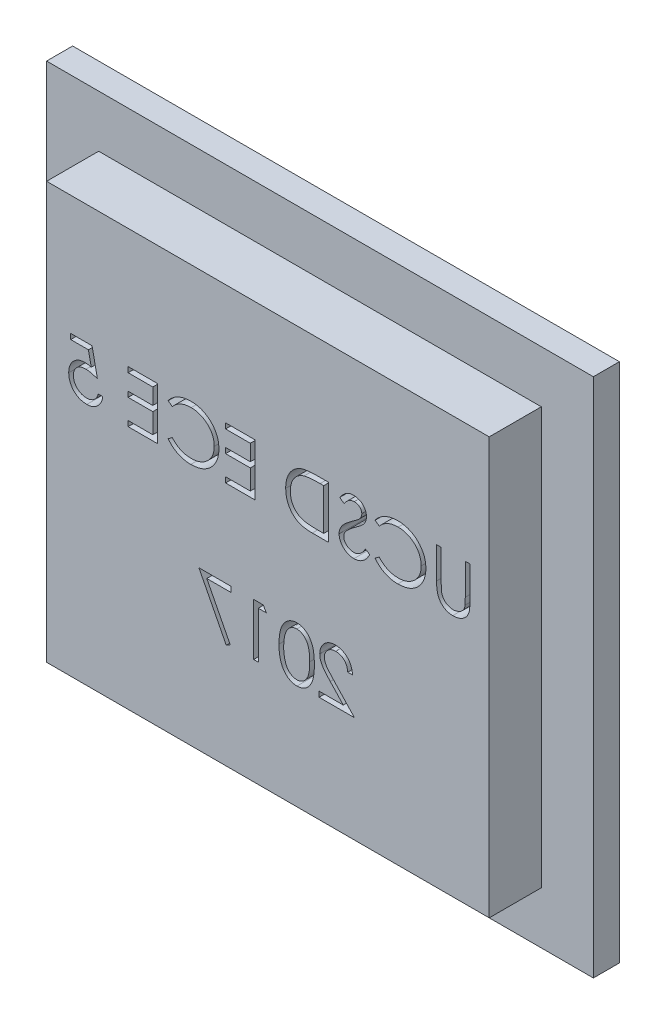
SolidWorks part; units mm, degrees
ref_plane "Front Plane" through (0, 0, 0) normal (0, 0, 1) x (1, 0, 0)
ref_plane "Top Plane" through (0, 0, 0) normal (0, 1, 0) x (1, 0, 0)
ref_plane "Right Plane" through (0, 0, 0) normal (1, 0, 0) x (0, 0, -1)
sketch "Sketch1" plane through (0, 0, 0) normal (0, 0, 1) x (1, 0, 0)
  line L1 (-5.25, -5) -> (5.25, -5)
  line L2 (-5.25, -5) -> (-5.25, 5)
  line L3 (-5.25, 5) -> (5.25, 5)
  line L4 (5.25, -5) -> (5.25, 5)
  line L5 (-5.25, -5) -> (5.25, 5) construction
  line L6 (-5.25, 5) -> (5.25, -5) construction
  point P0 (0, 0)
  dimension "D1" = 10
  dimension "D2" = 10.5
extrude "Boss-Extrude1" add sketch "Sketch1" along normal blind 0.5
sketch "Sketch2" plane through (0, 0, 0.5) normal (0, 0, 1) x (1, 0, 0)
  line L1 (-4.25, -4) -> (4.25, -4)
  line L2 (-4.25, -4) -> (-4.25, 4)
  line L3 (-4.25, 4) -> (4.25, 4)
  line L4 (4.25, -4) -> (4.25, 4)
  line L5 (-4.25, -4) -> (4.25, 4) construction
  line L6 (-4.25, 4) -> (4.25, -4) construction
  point P0 (0, 0)
  dimension "D1" = 8
  dimension "D2" = 8.5
extrude "Boss-Extrude2" add sketch "Sketch2" along normal blind 1
sketch "Sketch3" plane through (0, 0, 0) normal (0, 0, -1) x (-1, 0, 0)
  text T0 "UCSD ECE 5\r\n      2017" font "Century Gothic" height 1
extrude "Cut-Extrude1" cut sketch "Sketch3" against normal through all both and the other way through all
